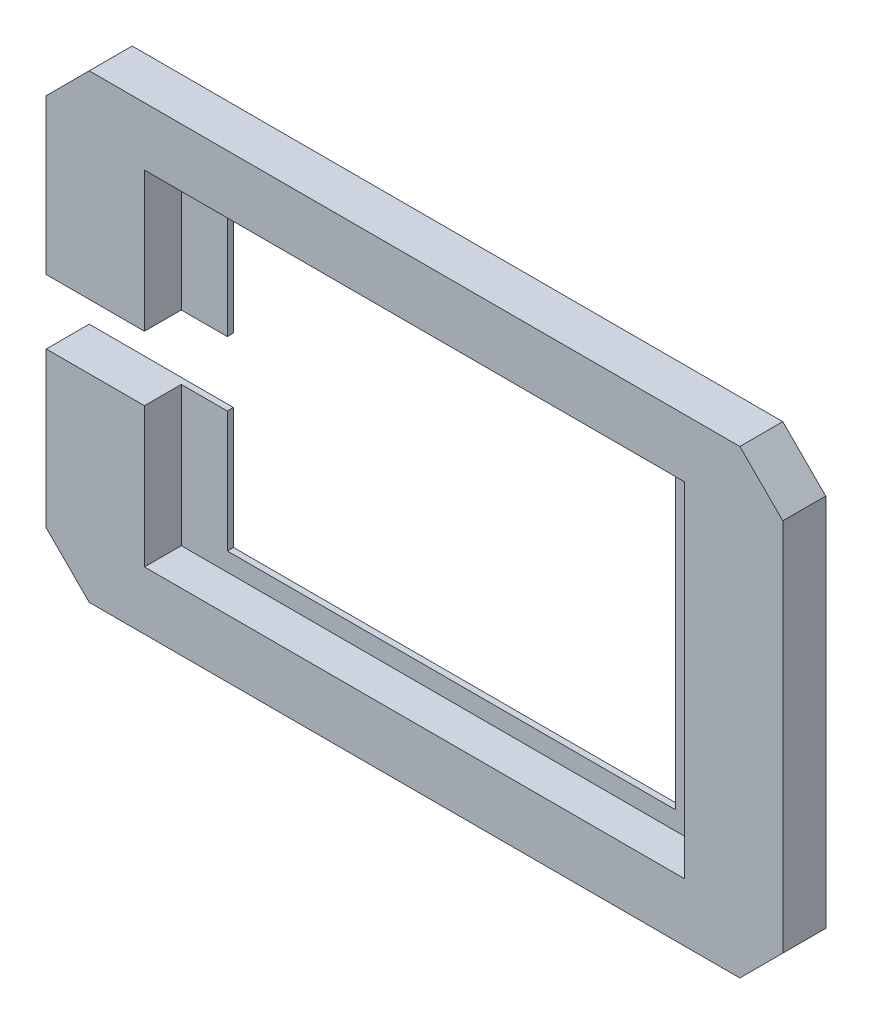
SolidWorks part; units mm, degrees
ref_plane "Alzado" through (0, 0, 0) normal (0, 0, 1) x (1, 0, 0)
ref_plane "Planta" through (0, 0, 0) normal (0, 1, 0) x (1, 0, 0)
ref_plane "Vista lateral" through (0, 0, 0) normal (1, 0, 0) x (0, 0, -1)
sketch "Croquis1" plane through (0, 0, 0) normal (0, 0, 1) x (1, 0, 0)
  line L1 (60, -37.5) -> (-60, -37.5)
  line L2 (60, -37.5) -> (60, 37.5)
  line L3 (60, 37.5) -> (-60, 37.5)
  line L4 (-60, -37.5) -> (-60, 37.5)
  line L5 (60, -37.5) -> (-60, 37.5) construction
  line L6 (60, 37.5) -> (-60, -37.5) construction
  point P0 (0, 0)
  dimension "D1" = 120
  dimension "D2" = 75
extrude "Saliente-Extruir1" add sketch "Croquis1" along normal blind 7
sketch "Croquis2" plane through (0, 0, 0) normal (0, 0, -1) x (-1, 0, 0)
  line L1 (-36.5, -25) -> (36.5, -25)
  line L2 (-36.5, -25) -> (-36.5, 25)
  line L3 (-36.5, 25) -> (36.5, 25)
  line L4 (36.5, -25) -> (36.5, 25)
  line L5 (-36.5, -25) -> (36.5, 25) construction
  line L6 (-36.5, 25) -> (36.5, -25) construction
  point P0 (0, 0)
  dimension "D1" = 73
  dimension "D2" = 50
extrude "Cortar-Extruir1" cut sketch "Croquis2" against normal blind 15
sketch "Croquis3" plane through (0, 0, 7) normal (0, 0, 1) x (1, 0, 0)
  line L1 (44, -28) -> (-44, -28)
  line L2 (44, -28) -> (44, 28)
  line L3 (44, 28) -> (-44, 28)
  line L4 (-44, -28) -> (-44, 28)
  line L5 (44, -28) -> (-44, 28) construction
  line L6 (44, 28) -> (-44, -28) construction
  point P0 (0, 0)
  dimension "D1" = 88
  dimension "D2" = 56
extrude "Cortar-Extruir2" cut sketch "Croquis3" against normal blind 6
sketch "Croquis4" plane through (0, 0, 0) normal (0, 0, -1) x (-1, 0, 0)
  line L0 (60, -5.25) -> (36.5, -5.25)
  line L1 (60, 37.5) -> (60, -37.5) construction
  line L2 (36.5, -25) -> (36.5, 25) construction
  line L3 (36.5, -5.25) -> (36.5, 5.25)
  line L4 (36.5, 5.25) -> (60, 5.25)
  line L5 (60, 5.25) -> (60, -5.25)
  dimension "D1" = 10.5
  dimension "D2" = 5.25
extrude "Cortar-Extruir3" cut sketch "Croquis4" against normal blind 25
chamfer "Chaflán3" distance 7 angle 45 4 edges at (60, -37.5, 3.5) (60, 37.5, 3.5) (-60, -37.5, 3.5) (-60, 37.5, 3.5)
